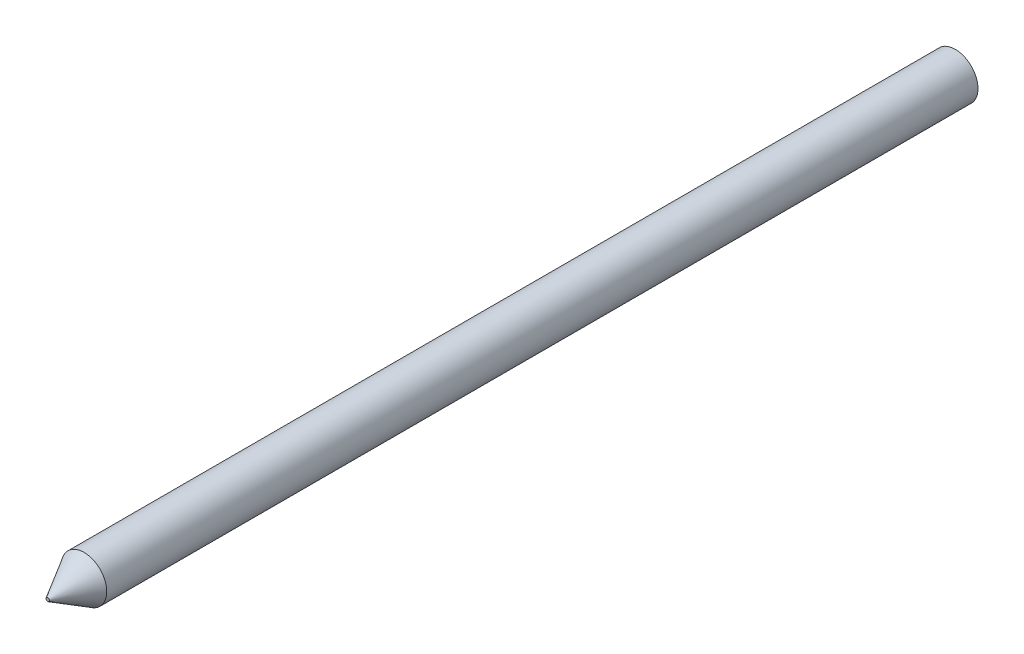
SolidWorks part; units mm, degrees
ref_plane "Front Plane" through (0, 0, 0) normal (0, 0, 1) x (1, 0, 0)
ref_plane "Top Plane" through (0, 0, 0) normal (0, 1, 0) x (1, 0, 0)
ref_plane "Right Plane" through (0, 0, 0) normal (1, 0, 0) x (0, 0, -1)
sketch "Sketch1" plane through (0, 0, 0) normal (0, 0, 1) x (1, 0, 0)
  circle A0 centre (-59.4674, 37.1242) radius 6.35
extrude "Boss-Extrude2" add sketch "Sketch1" along normal blind 254 contours A0
chamfer "Chamfer7" distance 10.16 angle 30 1 edges at (-53.1174, 37.1242, 254)
